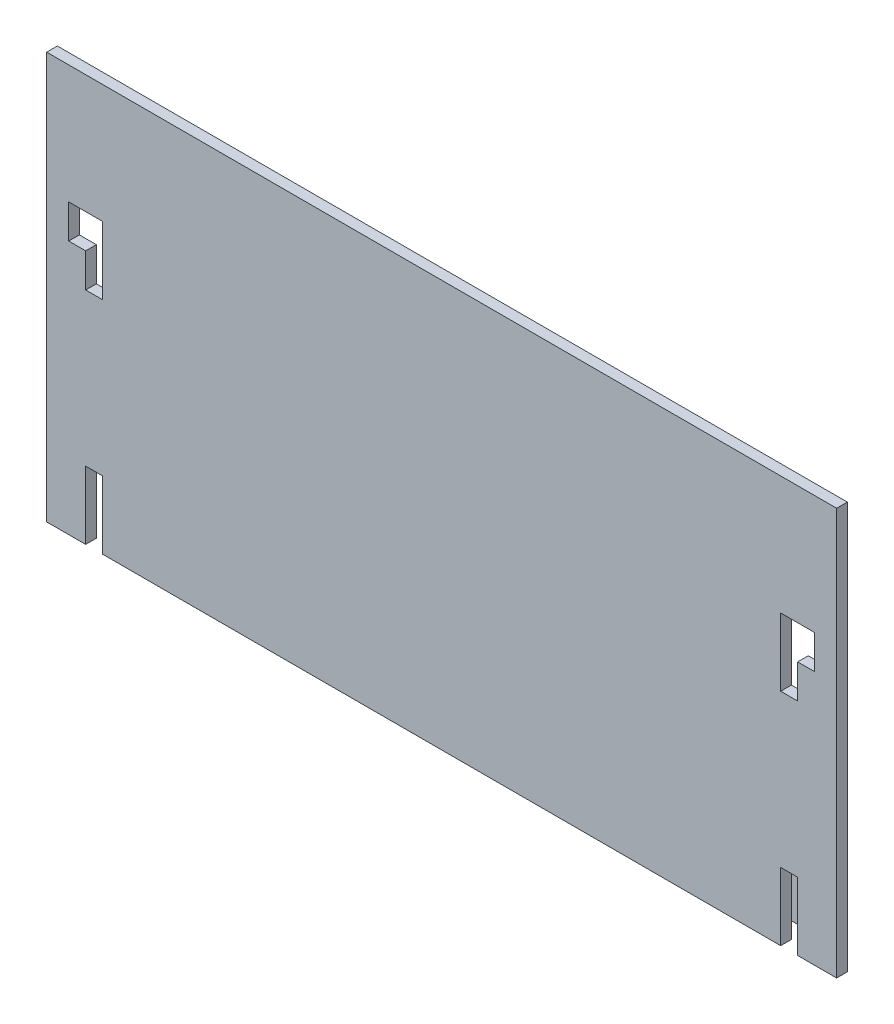
SolidWorks part; units mm, degrees
ref_plane "Front Plane" through (0, 0, 0) normal (0, 0, 1) x (1, 0, 0)
ref_plane "Top Plane" through (0, 0, 0) normal (0, 1, 0) x (1, 0, 0)
ref_plane "Right Plane" through (0, 0, 0) normal (1, 0, 0) x (0, 0, -1)
sketch "Sketch1" plane through (0, 0, 0) normal (1, 0, 0) x (0, 0, -1)
  line L0 (1.524, -12.7) -> (1.524, 0)
  line L1 (1.524, 0) -> (-1.524, 0)
  line L2 (-1.524, 0) -> (-1.524, -12.7)
  line L3 (-1.524, -12.7) -> (-3.524, -12.7)
  line L4 (-3.524, -12.7) -> (-3.524, 63.5)
  line L5 (-3.524, 63.5) -> (3.524, 63.5)
  line L6 (3.524, 63.5) -> (3.524, -12.7)
  line L7 (3.524, -12.7) -> (1.524, -12.7)
  line L9 (3.524, 63.5) -> (-1.524, 63.5)
  line L10 (3.524, 63.5) -> (3.524, 3.175)
  line L11 (3.524, 3.175) -> (1.651, 3.175)
  line L12 (-1.524, 63.5) -> (-1.524, 6.35)
  arc A0 (1.651, 3.175) -> (-1.524, 6.35) centre (1.651, 6.35) cw
  point P7 (0, 0)
  dimension "D7" = 3.175
  dimension "D1" = 2
  dimension "D2" = 3.048
  dimension "D3" = 12.7
  dimension "D4" = 63.5
  dimension "D5" = 2
  dimension "D6" = 3.175
extrude "Boss-Extrude1" add sketch "Sketch1" along normal blind 147.955 contours L11 A0 L12 L5 L4 L3 L2 L1 L0 L7 L6
sketch "Sketch2" plane through (0, 0, 1.524) normal (0, 0, -1) x (-1, 0, 0)
  line L0 (-147.955, -12.7) -> (0, -12.7) construction
  line L1 (-147.955, 6.35) -> (-137.4775, 6.35)
  line L2 (-147.955, 6.35) -> (-147.955, -12.7)
  line L3 (-147.955, -12.7) -> (-137.4775, -12.7)
  line L4 (-137.4775, 6.35) -> (-137.4775, -12.7)
  line L6 (0, 6.35) -> (-10.4775, 6.35)
  line L7 (0, 6.35) -> (0, -12.7)
  line L8 (0, -12.7) -> (-10.4775, -12.7)
  line L9 (-10.4775, 6.35) -> (-10.4775, -12.7)
  dimension "D1" = 127
extrude "Cut-Extrude1" cut sketch "Sketch2" along normal through all
sketch "Sketch3" plane through (0, 0, 1.524) normal (0, 0, -1) x (-1, 0, 0)
  line L0 (-147.955, -12.7) -> (0, -12.7) construction
  line L1 (-137.4775, 0) -> (-140.6525, 0)
  line L2 (-137.4775, 0) -> (-137.4775, -12.7)
  line L3 (-137.4775, -12.7) -> (-140.6525, -12.7)
  line L4 (-140.6525, 0) -> (-140.6525, -12.7)
  line L6 (-10.4775, 0) -> (-7.3025, 0)
  line L7 (-10.4775, 0) -> (-10.4775, -12.7)
  line L8 (-10.4775, -12.7) -> (-7.3025, -12.7)
  line L9 (-7.3025, 0) -> (-7.3025, -12.7)
  point P12 (0, 0)
  point P13 (-137.4775, 3.175)
  point P14 (-137.4775, 0)
  point P15 (0, 0)
  point P16 (0, 0)
  point P18 (-7.1274, -4.9176)
  point P19 (-8.375, -4.0227)
  point P20 (-10.4775, 0)
  dimension "D1" = 3.175
extrude "Cut-Extrude2" cut sketch "Sketch3" against normal through all
sketch "Sketch4" plane through (0, 0, 1.524) normal (0, 0, -1) x (-1, 0, 0)
  line L0 (-140.6525, 31.75) -> (-139.065, 31.75) construction
  line L11 (-139.065, 0) -> (-139.065, 63.5) construction
  line L12 (-137.4775, 0) -> (-140.6525, 0) construction
  line L13 (-147.955, 63.5) -> (0, 63.5) construction
  line L14 (-8.89, 0) -> (-8.89, 63.5) construction
  line L15 (-7.3025, 0) -> (-10.4775, 0) construction
  line L16 (-137.4775, 34.925) -> (-143.8275, 34.925)
  line L17 (-140.6525, 34.925) -> (-137.4775, 34.925)
  line L18 (-140.6525, 34.925) -> (-140.6525, 28.575)
  line L19 (-140.6525, 28.575) -> (-137.4775, 28.575)
  line L20 (-137.4775, 34.925) -> (-137.4775, 28.575)
  line L21 (-10.4775, 34.925) -> (-7.3025, 34.925)
  line L22 (-10.4775, 34.925) -> (-10.4775, 28.575)
  line L23 (-10.4775, 28.575) -> (-7.3025, 28.575)
  line L24 (-7.3025, 34.925) -> (-7.3025, 28.575)
  line L29 (-137.4775, 34.925) -> (-137.4775, 41.275)
  line L30 (-137.4775, 41.275) -> (-143.8275, 41.275)
  line L31 (-143.8275, 34.925) -> (-143.8275, 41.275)
  line L32 (-10.4775, 34.925) -> (-4.1275, 34.925)
  line L33 (-10.4775, 34.925) -> (-10.4775, 41.275)
  line L34 (-10.4775, 41.275) -> (-4.1275, 41.275)
  line L35 (-4.1275, 34.925) -> (-4.1275, 41.275)
  point P18 (-8.89, 34.925)
  point P22 (-139.065, 34.925)
  point P23 (-140.6525, 24.4778)
  point P26 (-140.6525, 31.75)
  point P30 (0, 0)
  point P31 (-139.065, 31.75)
  dimension "D1" = 3.175
  dimension "D2" = 6.35
extrude "Cut-Extrude3" cut sketch "Sketch4" against normal through all contours L31 L16 L29 L30 | L20 L16 L18 L19 | L32 L35 L34 L33 L21 | L24 L21 L22 L23
